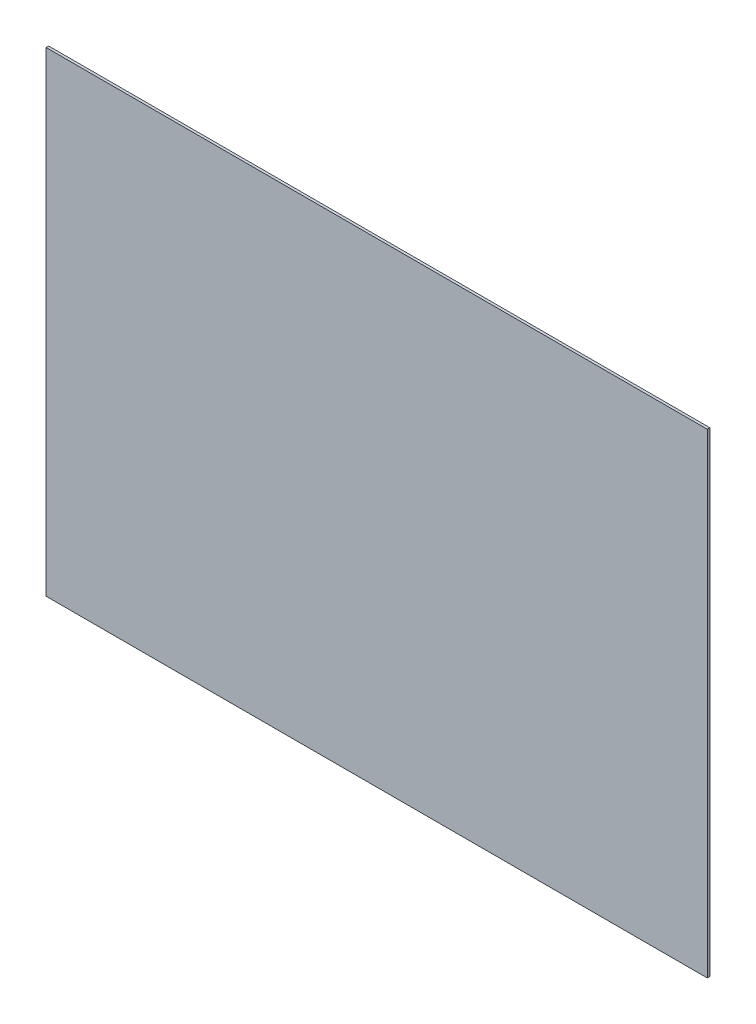
SolidWorks part; units mm, degrees
ref_plane "Front Plane" through (0, 0, 0) normal (0, 0, 1) x (1, 0, 0)
ref_plane "Top Plane" through (0, 0, 0) normal (0, 1, 0) x (1, 0, 0)
ref_plane "Right Plane" through (0, 0, 0) normal (1, 0, 0) x (0, 0, -1)
sketch "Sketch1" plane through (0, 0, 0) normal (0, 0, 1) x (1, 0, 0)
  line L1 (0, 0) -> (812.8, 0)
  line L2 (0, 0) -> (0, 584.2)
  line L3 (0, 584.2) -> (812.8, 584.2)
  line L4 (812.8, 0) -> (812.8, 584.2)
  dimension "D1" = 584.2
  dimension "D2" = 812.8
extrude "Boss-Extrude1" add sketch "Sketch1" along normal blind 3.175
